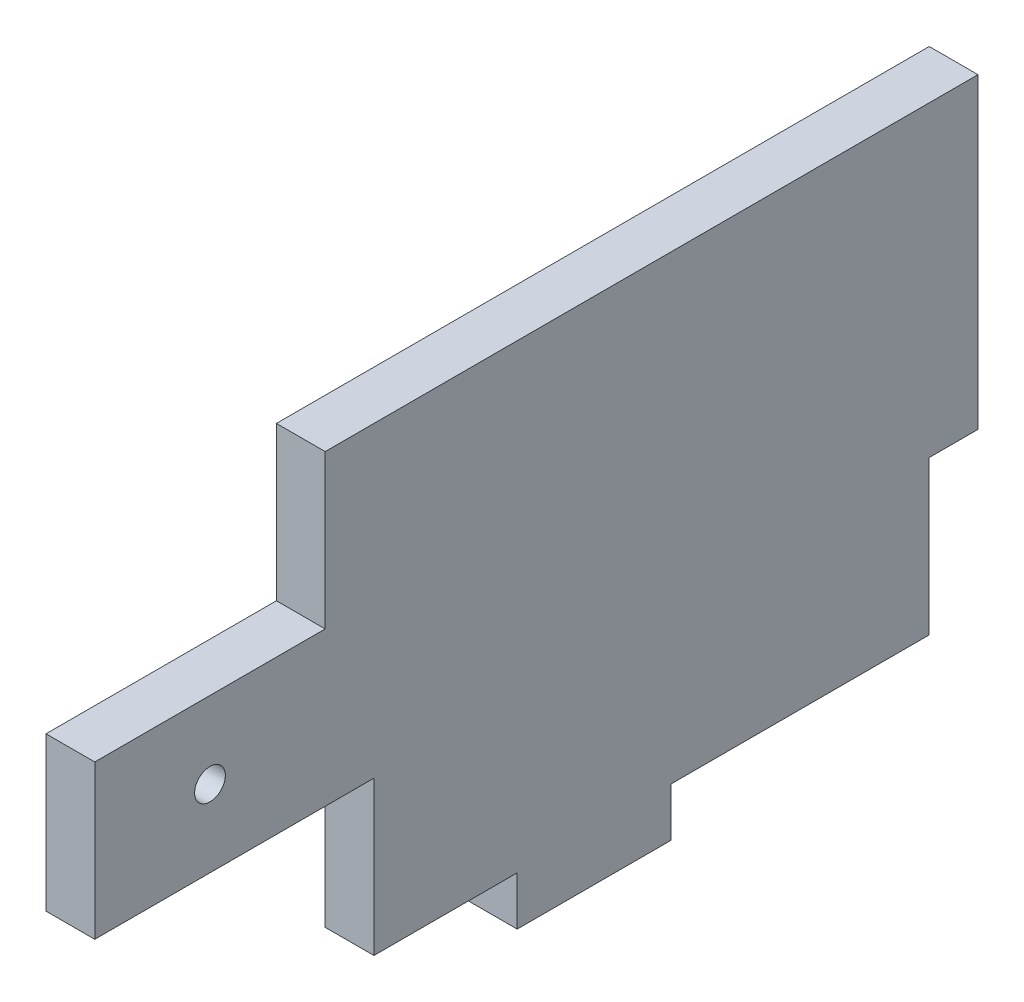
SolidWorks part; units mm, degrees
ref_plane "Front Plane" through (0, 0, 0) normal (0, 0, 1) x (1, 0, 0)
ref_plane "Top Plane" through (0, 0, 0) normal (0, 1, 0) x (1, 0, 0)
ref_plane "Right Plane" through (0, 0, 0) normal (1, 0, 0) x (0, 0, -1)
sketch "Sketch1" plane through (0, 0, 0) normal (1, 0, 0) x (0, 0, -1)
  line L1 (-85, -60) -> (85, -60)
  line L2 (-85, -60) -> (-85, 60)
  line L3 (-85, 60) -> (85, 60)
  line L4 (85, -60) -> (85, 60)
  line L5 (-85, -60) -> (85, 60) construction
  line L6 (-85, 60) -> (85, -60) construction
  line L7 (-35, -60) -> (5, -60)
  line L8 (-35, -60) -> (-35, -72.7)
  line L9 (-35, -72.7) -> (5, -72.7)
  line L10 (5, -60) -> (5, -72.7)
  line L15 (-85, -20) -> (-145, -20)
  line L16 (-85, -20) -> (-85, 20)
  line L17 (-85, 20) -> (-145, 20)
  line L18 (-145, -20) -> (-145, 20)
  point P0 (0, 0)
  dimension "D1" = 170
  dimension "D2" = 120
  dimension "D3" = 12.7
  dimension "D4" = 40
  dimension "D5" = 50
  dimension "D6" = 60
  dimension "D7" = 40
  dimension "D8" = 40
extrude "Boss-Extrude1" add sketch "Sketch1" along normal blind 12.7 contours L1 L4 L3 L2 | L8 L9 L10 L7 | L16 L15 L18 L17
sketch "Sketch2" plane through (12.7, 0, 0) normal (1, 0, 0) x (0, 0, -1)
  line L0 (-145, -20) -> (-145, 20) construction
  line L1 (-85, -60) -> (-72.3, -60)
  line L2 (-85, -60) -> (-85, -20)
  line L3 (-85, -20) -> (-72.3, -20)
  line L4 (-72.3, -60) -> (-72.3, -20)
  line L5 (85, -60) -> (72.3, -60)
  line L6 (85, -60) -> (85, -20)
  line L7 (85, -20) -> (72.3, -20)
  line L8 (72.3, -60) -> (72.3, -20)
  line L9 (-85, -20) -> (-145, -20) construction
  circle A0 centre (-115, 0) radius 4
  dimension "D3" = 8
  dimension "D1" = 12.7
  dimension "D2" = 40
  dimension "D4" = 30
  dimension "D5" = 20
  dimension "D6" = 12.7
  dimension "D7" = 40
extrude "Cut-Extrude1" cut sketch "Sketch2" against normal blind 12.7
